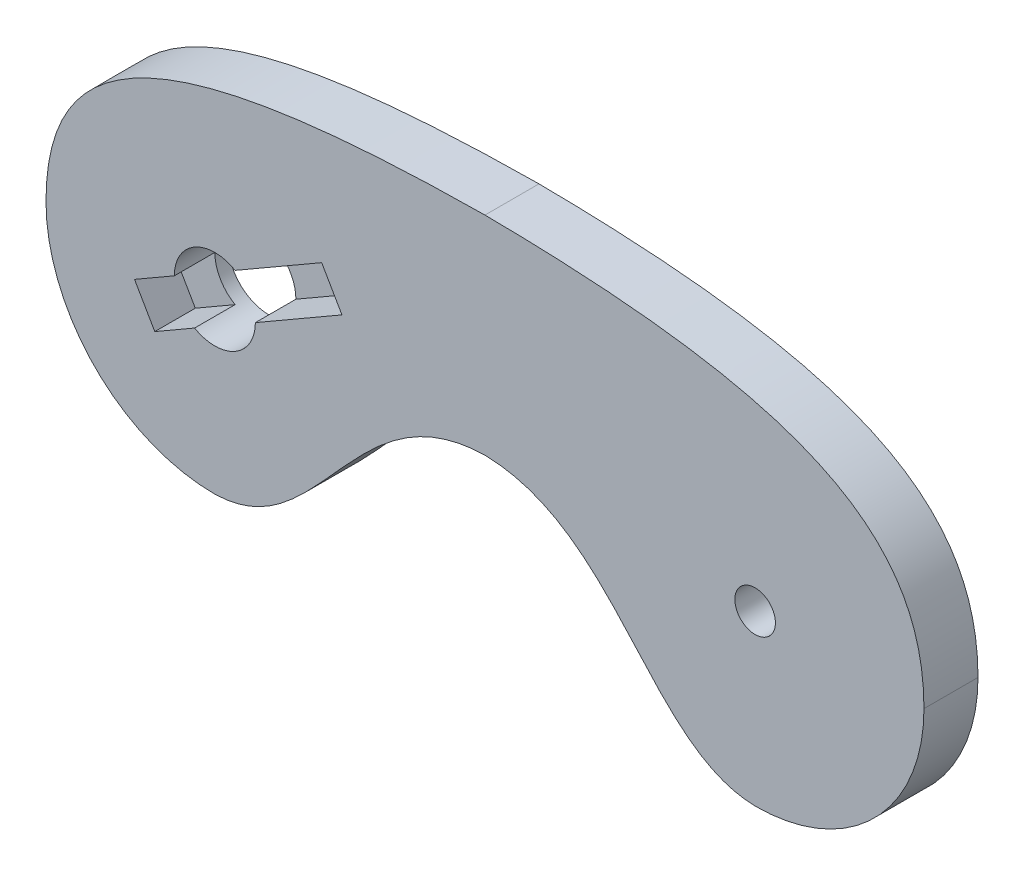
SolidWorks part; units mm, degrees
ref_plane "前视基准面" through (0, 0, 0) normal (0, 0, 1) x (1, 0, 0)
ref_plane "上视基准面" through (0, 0, 0) normal (0, 1, 0) x (1, 0, 0)
ref_plane "右视基准面" through (0, 0, 0) normal (1, 0, 0) x (0, 0, -1)
sketch "草图1" plane through (0, 0, 0) normal (0, 0, 1) x (1, 0, 0)
  line L0 (60, 0) -> (100, 0) construction
  line L9 (57.4019, 1.5) -> (53, 1.5) construction
  line L10 (62.5981, -1.5) -> (69, -1.5) construction
  line L11 (69, 1.5) -> (62.5981, 1.5) construction
  line L12 (69, -1.5) -> (69, 1.5) construction
  line L13 (80, 0) -> (80, 30.7931) construction
  line L14 (53, -1.5) -> (57.4019, -1.5) construction
  line L15 (53, 0) -> (53, 1.5) construction
  line L16 (53, 0) -> (53, -1.5) construction
  circle A0 centre (60, 0) radius 12.5 construction
  circle A1 centre (100, 0) radius 1.5
  circle A4 centre (60, 0) radius 1.5 construction
  circle A5 centre (100, 0) radius 12.5 construction
  circle A6 centre (60, 0) radius 3
  arc A7 (112.5, 0) -> (100, -12.5) centre (100, 0) cw
  arc A8 (60, -12.5) -> (47.5, 0) centre (60, 0) cw
  spline S4 degree 3 poles (100, -12.5) (92.1402, -12.329) (89.8252, -0.2226) (80, 0) knots 0 0 0 0 1 1 1 1
  spline S5 degree 3 poles (60, -12.5) (67.8598, -12.329) (70.1748, -0.2226) (80, 0) knots 0 0 0 0 1 1 1 1
  spline S6 degree 3 poles (112.5, 0) (112.5, 11.1158) (102.7647, 15.1709) (80, 15.3965) knots 0 0 0 0 1 1 1 1
  spline S7 degree 3 poles (47.5, 0) (47.5, 11.1158) (57.2353, 15.1709) (80, 15.3965) knots 0 0 0 0 1 1 1 1
  point P11 (47.5, 0)
  point P12 (53, 0)
  point P15 (69, 0)
  dimension "D3" = 12.5
  dimension "D1" = 40
  dimension "D4" = 7
  dimension "D5" = 9
extrude "凸台-拉伸1" add sketch "草图1" along normal blind 4
sketch "草图5" plane through (0, 0, 4) normal (0, 0, 1) x (1, 0, 0)
  line L0 (60, 0) -> (36.5391, 0) construction
  line L1 (54.8038, -3) -> (54.0538, -1.701)
  line L2 (54.0538, -1.701) -> (67.9103, 6.299)
  line L3 (54.8038, -3) -> (55.5538, -4.299)
  line L4 (55.5538, -4.299) -> (69.4103, 3.701)
  line L5 (69.4103, 3.701) -> (67.9103, 6.299)
  point P0 (60, 0)
  dimension "D1" = 6
  dimension "D2" = 1.5
  dimension "D3" = 16
  dimension "D4" = 1.5
extrude "切除-拉伸2" cut sketch "草图5" against normal blind 3
